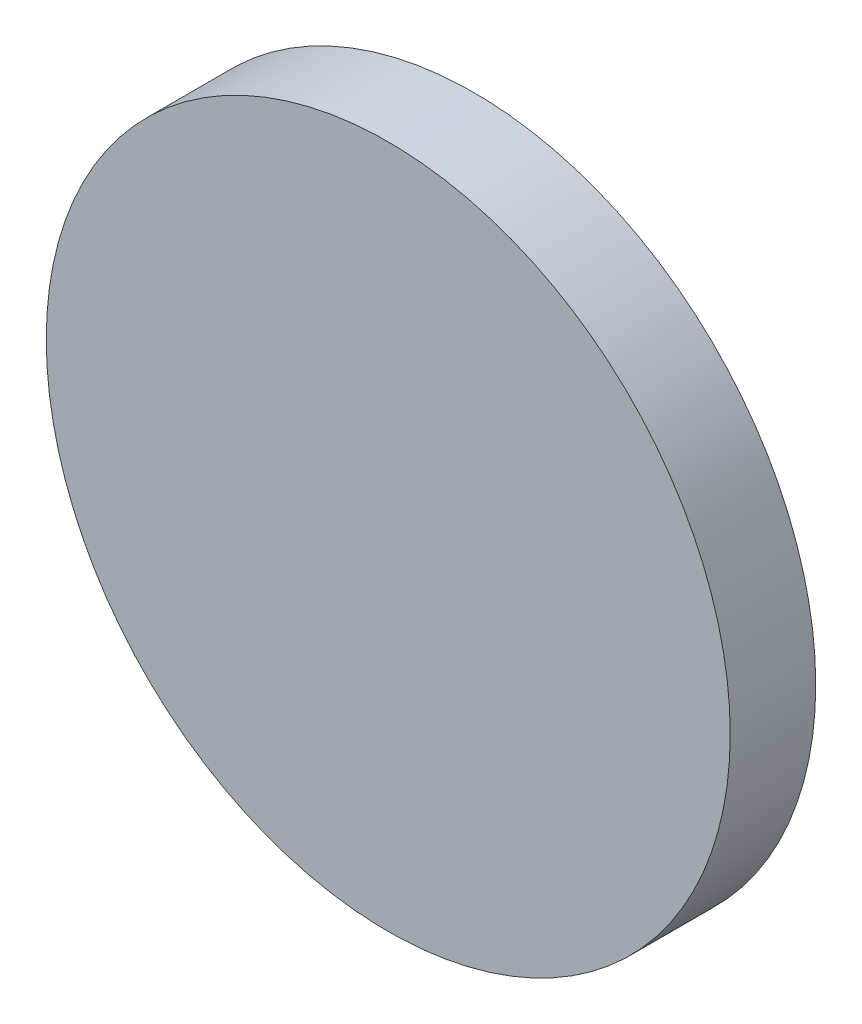
SolidWorks part; units mm, degrees
material "Beryllium Copper, UNS C17000"
ref_plane "Front Plane" through (0, 0, 0) normal (0, 0, 1) x (1, 0, 0)
ref_plane "Top Plane" through (0, 0, 0) normal (0, 1, 0) x (1, 0, 0)
ref_plane "Right Plane" through (0, 0, 0) normal (1, 0, 0) x (0, 0, -1)
sketch "Sketch1" plane through (0, 0, 0) normal (0, 0, 1) x (1, 0, 0)
  circle A0 centre (0, 0) radius 8
extrude "Boss-Extrude1" add sketch "Sketch1" along normal blind 2
